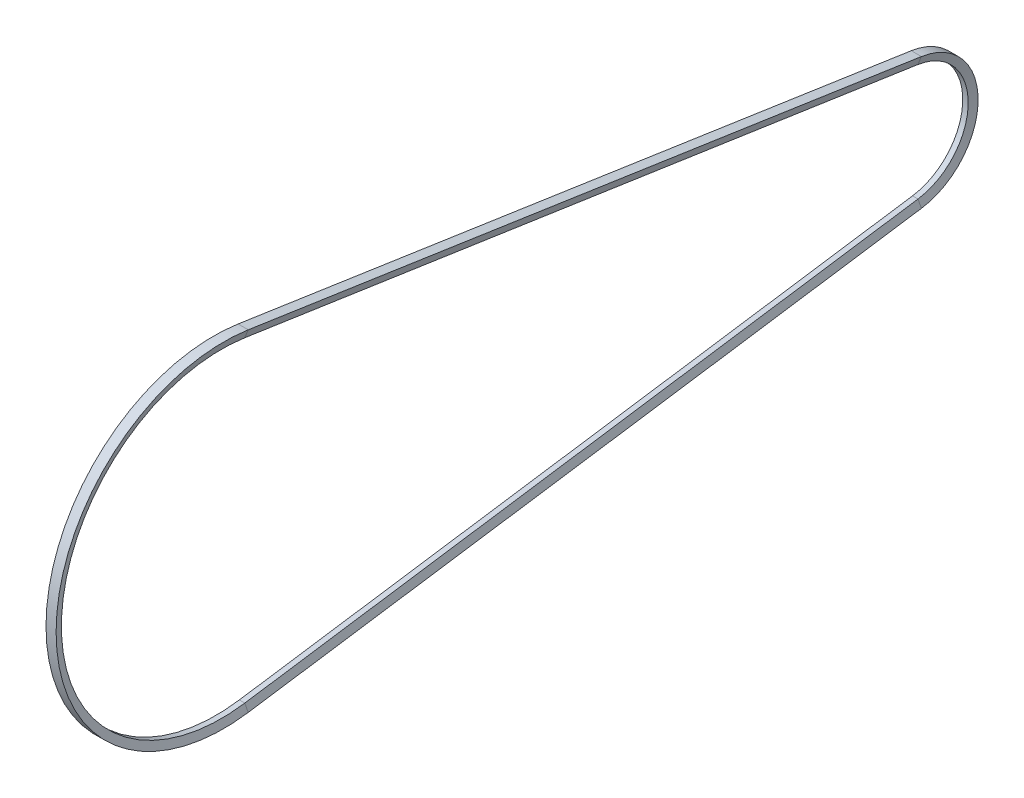
SolidWorks part; units mm, degrees
ref_plane "前视基准面" through (0, 0, 0) normal (0, 0, 1) x (1, 0, 0)
ref_plane "上视基准面" through (0, 0, 0) normal (0, 1, 0) x (1, 0, 0)
ref_plane "右视基准面" through (0, 0, 0) normal (1, 0, 0) x (0, 0, -1)
sketch "草图1" plane through (0, 0, 0) normal (1, 0, 0) x (0, 0, -1)
  line L0 (46.2587, 311.5849) -> (1312.1666, 123.6448)
  line L1 (46.2587, -311.5849) -> (1312.1666, -123.6448)
  line L2 (0, 0) -> (1293.81, 0) construction
  arc A0 (46.2587, 311.5849) -> (46.2587, -311.5849) centre (0, 0) ccw
  arc A1 (1312.1666, -123.6448) -> (1312.1666, 123.6448) centre (1293.81, 0) ccw
  dimension "D1" = 315
  dimension "D2" = 125
  dimension "D3" = 1293.81
sketch "草图2" plane through (0, 0, 0) normal (0, 0, 1) x (1, 0, 0)
  line L0 (-9.5, 315) -> (9.5, 315)
  line L1 (9.5, 315) -> (5.1281, 300.7)
  line L2 (5.1281, 300.7) -> (-5.1281, 300.7)
  line L3 (-5.1281, 300.7) -> (-9.5, 315)
  line L4 (0, 300.7) -> (0, 315) construction
  line L5 (0, -315) -> (0, 315) construction
  dimension "D1" = 19
  dimension "D2" = 14.3
  dimension "D3" = 34
sweep "扫描1" add profiles "草图2" path "草图1"
equation "\"D3@草图1\" = \"D1@距离1@实心轮_实心轮.Assembly\""
equation "\"D3@草图1\" = \"D1@距离1@实心轮_孔板轮.Assembly\""
equation "\"D3@草图1\" = \"D1@距离1@实心轮_辐板轮.Assembly\""
equation "\"D3@草图1\" = \"D1@距离1@孔板轮_孔板轮.Assembly\""
equation "\"D3@草图1\" = \"D1@距离1@孔板轮_辐板轮.Assembly\""
equation "\"D3@草图1\" = \"D1@距离1@辐板轮_辐板轮.Assembly\""
equation "\"D1@草图2\" = \"bd@草图1@小带轮_实心轮<1>.Part\""
equation "\"D1@草图2\" = \"bd@草图1@大带轮_孔板轮<1>.Part\""
equation "\"D1@草图2\" = \"bd@草图1@大带轮_辐板轮.Part\" "
equation "\"D2@草图2\" = \"hf@草图1@小带轮_实心轮<1>.Part\""
equation "\"D2@草图2\" = \"hf@草图1@大带轮_辐板轮.Part\" "
equation "\"D2@草图2\" = \"hf@草图1@大带轮_孔板轮<1>.Part\""
equation "\"D3@草图2\" = \"槽轮角@草图1@小带轮_实心轮<1>.Part\""
equation "\"D3@草图2\" = \"槽轮角@草图1@大带轮_辐板轮.Part\" "
equation "\"D3@草图2\" = \"槽轮角@草图1@大带轮_孔板轮<1>.Part\""
equation "\"D2@草图1\" = \"dd@草图1@小带轮_实心轮<1>.Part\" / 2"
equation " \"D2@草图1\" = \"dd@草图1@小带轮_孔板轮.Part\"/2"
equation "\"D2@草图1\" = \"dd@草图1@小带轮_辐板轮.Part\"/2  "
equation "\"D1@草图1\" = \"dd@草图1@大带轮_实心轮.Part\" /2"
equation "\"D1@草图1\" = \"dd@草图1@大带轮_孔板轮<1>.Part\" / 2"
equation "\"D1@草图1\" = \"dd@草图1@大带轮_辐板轮.Part\" /2"
